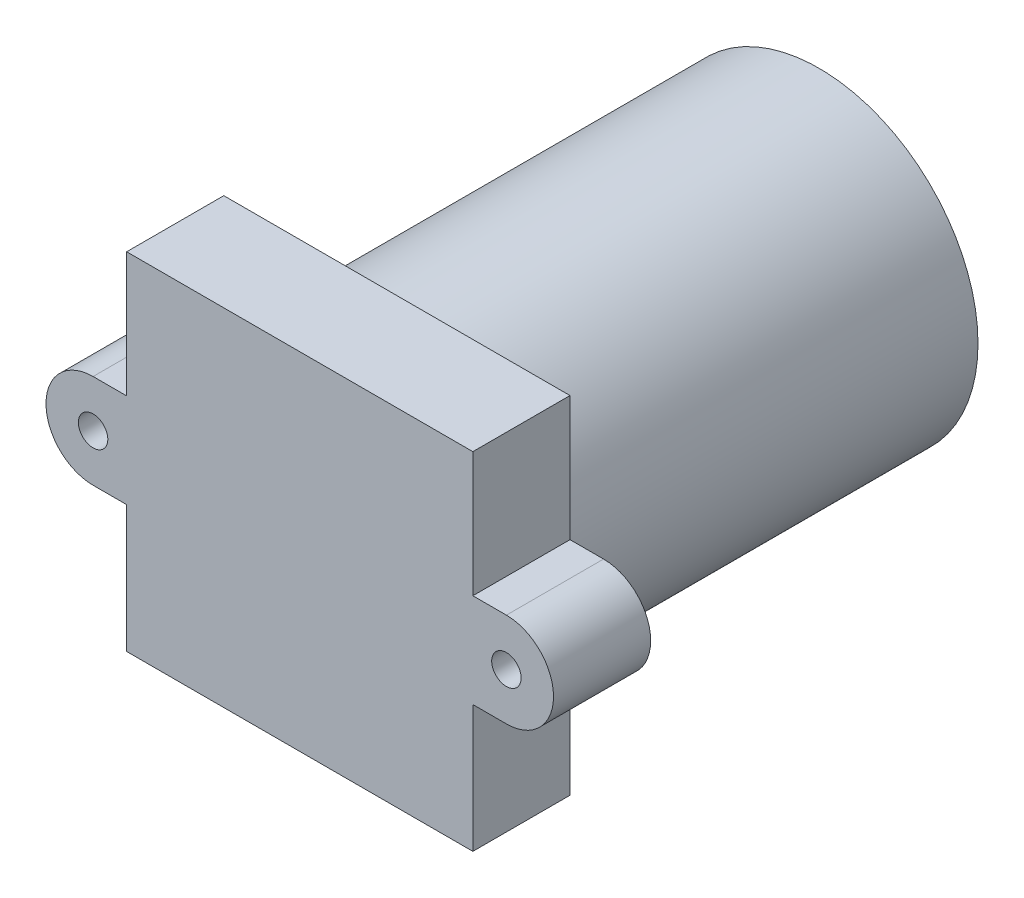
SolidWorks part; units mm, degrees
ref_plane "Front Plane" through (0, 0, 0) normal (0, 0, 1) x (1, 0, 0)
ref_plane "Top Plane" through (0, 0, 0) normal (0, 1, 0) x (1, 0, 0)
ref_plane "Right Plane" through (0, 0, 0) normal (1, 0, 0) x (0, 0, -1)
sketch "Sketch1" plane through (0, 0, 0) normal (0, 0, 1) x (1, 0, 0)
  circle A0 centre (0, 0) radius 6.858
  dimension "D1" = 13.716
extrude "Boss-Extrude1" add sketch "Sketch1" along normal blind 18.2118
sketch "Sketch2" plane through (0, 0, 18.2118) normal (0, 0, 1) x (1, 0, 0)
  line L0 (0, 7.4676) -> (0, -7.4676) construction
  line L1 (-7.4676, 7.4676) -> (7.4676, 7.4676)
  line L2 (-7.4676, 7.4676) -> (-7.4676, 2.0828)
  line L3 (-7.4676, -7.4676) -> (7.4676, -7.4676)
  line L4 (7.4676, 7.4676) -> (7.4676, 2.0828)
  line L5 (-7.4676, -1.9812) -> (-7.4676, -7.4676)
  line L6 (7.4676, 2.0828) -> (8.9154, 2.0828)
  line L8 (7.4676, -1.9812) -> (8.9154, -1.9812)
  line L10 (-7.4676, 2.0828) -> (-8.9154, 2.0828)
  line L11 (7.4676, -1.9812) -> (7.4676, -7.4676)
  line L12 (-7.4676, -1.9812) -> (-8.9154, -1.9812)
  arc A0 (8.9154, -1.9812) -> (8.9154, 2.0828) centre (8.9154, 0.0508) ccw
  arc A1 (-8.9154, 2.0828) -> (-8.9154, -1.9812) centre (-8.9154, 0.0508) ccw
  circle A2 centre (-8.9154, 0.0508) radius 0.635
  circle A3 centre (8.9154, 0.0508) radius 0.635
  dimension "D7" = 17.8308
  dimension "D9" = 2.032
  dimension "D10" = 2.032
  dimension "D12" = 1.27
  dimension "D13" = 1.27
  dimension "D1" = 14.9352
  dimension "D2" = 14.9352
  dimension "D3" = 5.3848
  dimension "D4" = 4.064
  dimension "D5" = 5.3848
  dimension "D6" = 4.064
  dimension "D8" = 1.4478
  dimension "D11" = 1.4478
extrude "Boss-Extrude2" add sketch "Sketch2" along normal blind 4.191
